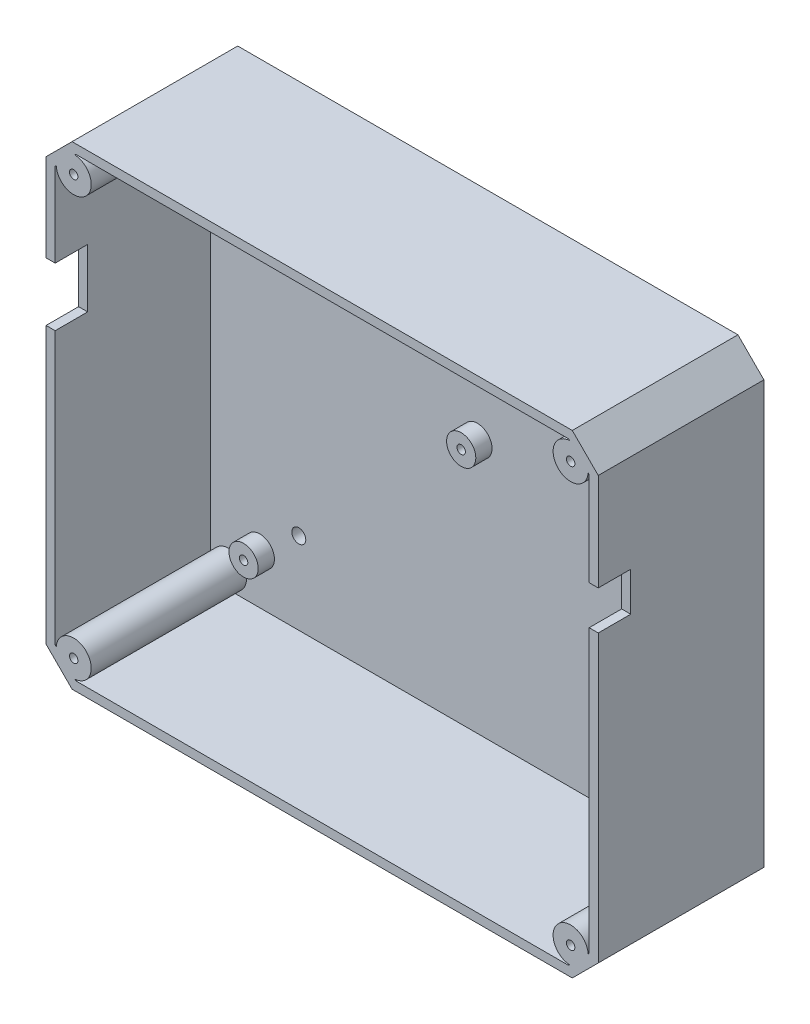
SolidWorks part; units mm, degrees
ref_plane "前视基准面" through (0, 0, 0) normal (0, 0, 1) x (1, 0, 0)
ref_plane "上视基准面" through (0, 0, 0) normal (0, 1, 0) x (1, 0, 0)
ref_plane "右视基准面" through (0, 0, 0) normal (1, 0, 0) x (0, 0, -1)
other "Configuration Table"
sketch "Floor 3.2 - four case mounting holes D4.3 profile" plane through (0, 0, 0) normal (0, 0, 1) x (1, 0, 0)
  line L0 (-77, -73) -> (77, -73)
  line L1 (77, -73) -> (85, -65)
  line L2 (85, -65) -> (85, 65)
  line L3 (85, 65) -> (77, 73)
  line L4 (77, 73) -> (-77, 73)
  line L5 (-77, 73) -> (-85, 65)
  line L6 (-85, 65) -> (-85, -65)
  line L7 (-85, -65) -> (-77, -73)
  circle A0 centre (-55, -45) radius 2.15
  circle A1 centre (-55, 45) radius 2.15
  circle A2 centre (55, -45) radius 2.15
  circle A3 centre (55, 45) radius 2.15
extrude "Floor 3.2 - four case mounting holes D4.3" add sketch "Floor 3.2 - four case mounting holes D4.3 profile" along normal blind 3.2
sketch "Perimeter wall 2.8 profile" plane through (0, 0, 0) normal (0, 0, 1) x (1, 0, 0)
  line L0 (-77, -73) -> (77, -73)
  line L1 (77, -73) -> (85, -65)
  line L2 (85, -65) -> (85, 65)
  line L3 (85, 65) -> (77, 73)
  line L4 (77, 73) -> (-77, 73)
  line L5 (-77, 73) -> (-85, 65)
  line L6 (-85, 65) -> (-85, -65)
  line L7 (-85, -65) -> (-77, -73)
  line L8 (-75.84, -70.2) -> (75.84, -70.2)
  line L9 (75.84, -70.2) -> (82.2, -63.84)
  line L10 (82.2, -63.84) -> (82.2, 63.84)
  line L11 (82.2, 63.84) -> (75.84, 70.2)
  line L12 (75.84, 70.2) -> (-75.84, 70.2)
  line L13 (-75.84, 70.2) -> (-82.2, 63.84)
  line L14 (-82.2, 63.84) -> (-82.2, -63.84)
  line L15 (-82.2, -63.84) -> (-75.84, -70.2)
extrude "Perimeter wall 2.8" add sketch "Perimeter wall 2.8 profile" along normal blind 47.8 from offset 3.2
sketch "Lid post cores profile" plane through (0, 0, 0) normal (0, 0, 1) x (1, 0, 0)
  circle A0 centre (-76.5, -64.5) radius 5.4
  circle A1 centre (-76.5, 64.5) radius 5.4
  circle A2 centre (76.5, -64.5) radius 5.4
  circle A3 centre (76.5, 64.5) radius 5.4
extrude "Lid post cores" add sketch "Lid post cores profile" along normal blind 37.8 from offset 3.2
sketch "Lid post tips - D2.6 pilot x 10 profile" plane through (0, 0, 0) normal (0, 0, 1) x (1, 0, 0)
  circle A0 centre (-76.5, -64.5) radius 5.4
  circle A1 centre (-76.5, 64.5) radius 5.4
  circle A2 centre (76.5, -64.5) radius 5.4
  circle A3 centre (76.5, 64.5) radius 5.4
  circle A4 centre (-76.5, -64.5) radius 1.3
  circle A5 centre (-76.5, 64.5) radius 1.3
  circle A6 centre (76.5, -64.5) radius 1.3
  circle A7 centre (76.5, 64.5) radius 1.3
extrude "Lid post tips - D2.6 pilot x 10" add sketch "Lid post tips - D2.6 pilot x 10 profile" along normal blind 10 from offset 41
sketch "Tray supports - D2.6 pilot x 5 profile" plane through (0, 0, 0) normal (0, 0, 1) x (1, 0, 0)
  circle A0 centre (-67, -55) radius 4.5
  circle A1 centre (-67, 54) radius 4.5
  circle A2 centre (67, -55) radius 4.5
  circle A3 centre (67, 54) radius 4.5
  circle A4 centre (0, 8) radius 4.5
  circle A5 centre (70, 33) radius 4.5
  circle A6 centre (-67, -55) radius 1.3
  circle A7 centre (-67, 54) radius 1.3
  circle A8 centre (67, -55) radius 1.3
  circle A9 centre (67, 54) radius 1.3
  circle A10 centre (0, 8) radius 1.3
  circle A11 centre (70, 33) radius 1.3
extrude "Tray supports - D2.6 pilot x 5" add sketch "Tray supports - D2.6 pilot x 5 profile" along normal blind 5 from offset 3.2
sketch "Cable exits 18 x 10 and 12 x 10 profile" plane through (0, 0, 0) normal (0, 0, 1) x (1, 0, 0)
  line L0 (-87, 20) -> (-81, 20)
  line L1 (-81, 20) -> (-81, 38)
  line L2 (-81, 38) -> (-87, 38)
  line L3 (-87, 38) -> (-87, 20)
  line L4 (81, 23) -> (87, 23)
  line L5 (87, 23) -> (87, 35)
  line L6 (87, 35) -> (81, 35)
  line L7 (81, 35) -> (81, 23)
extrude "Cable exits 18 x 10 and 12 x 10" cut sketch "Cable exits 18 x 10 and 12 x 10 profile" against normal blind 10 from offset 51
